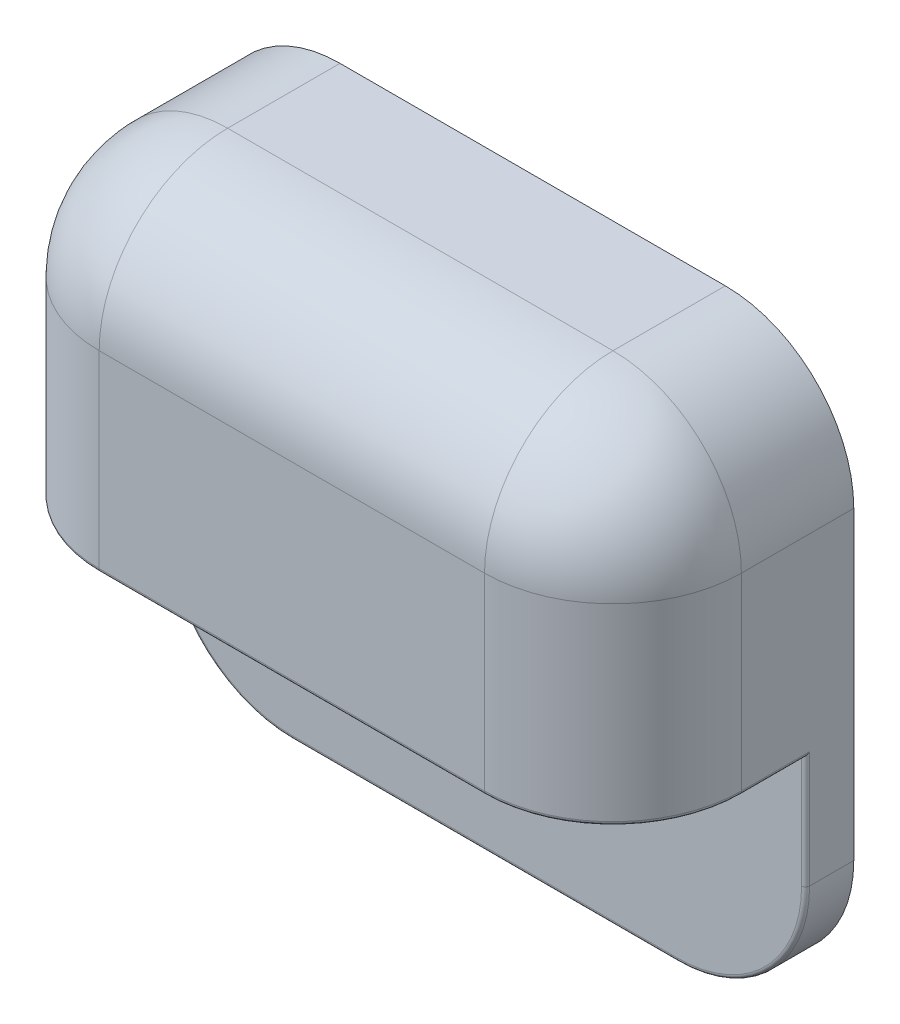
SolidWorks part; units mm, degrees
material "Plastique personnalisé"
ref_plane "Plan de face" through (0, 0, 0) normal (0, 0, 1) x (1, 0, 0)
ref_plane "Plan de dessus" through (0, 0, 0) normal (0, 1, 0) x (1, 0, 0)
ref_plane "Plan de droite" through (0, 0, 0) normal (1, 0, 0) x (0, 0, -1)
sketch "Esquisse1" plane through (0, 0, 0) normal (0, 0, 1) x (1, 0, 0)
  line L1 (-20, -10) -> (20, -10)
  line L2 (-20, -10) -> (-20, 10)
  line L3 (-20, 10) -> (20, 10)
  line L4 (20, -10) -> (20, 10)
  line L5 (-20, -10) -> (20, 10) construction
  line L6 (-20, 10) -> (20, -10) construction
  point P0 (0, 0)
  dimension "D1" = 20
  dimension "D2" = 40
extrude "Boss.-Extru.1" add sketch "Esquisse1" along normal blind 4 and the other way blind 8
sketch "Esquisse2" plane through (0, -10, 0) normal (0, -1, 0) x (1, 0, 0)
  line L0 (-20, -2) -> (20, -2) construction
  line L1 (-20, -8) -> (-20, 4) construction
  line L2 (20, -8) -> (20, 4) construction
  circle A0 centre (-13.7761, -2) radius 2.65
  circle A1 centre (-4.7761, -2) radius 2.65
  circle A2 centre (4.2239, -2) radius 2.65
  circle A3 centre (13.2239, -2) radius 2.65
  dimension "D1" = 4
extrude "Enlèv. mat.-Extru.1" cut sketch "Esquisse2" against normal blind 14.5
fillet "Congé1" radius 8 2 edges at (-20, 0, 4) (20, 0, 4)
fillet "Congé2" radius 0.25 4 edges at (13.2239, -10, -4.65) (4.2239, -10, -4.65) (-4.7761, -10, -4.65) (-13.7761, -10, -4.65)
sketch "Esquisse3" plane through (0, 0, -8) normal (0, 0, -1) x (-1, 0, 0)
  line L1 (20, 10) -> (-20, 10)
  line L2 (20, 10) -> (20, -25)
  line L3 (20, -25) -> (-20, -25)
  line L4 (-20, 10) -> (-20, -25)
  dimension "D1" = 35
extrude "Boss.-Extru.2" add sketch "Esquisse3" along normal blind 3
fillet "Congé3" radius 8 7 edges at (-20, 10, -7.5) (-17.6569, 10, 1.6569) (0, 10, 4) (20, 10, -7.5) (17.6569, 10, 1.6569) (-20, -25, -9.5) (20, -25, -9.5)
fillet "Congé4" radius 0.25 10 edges at (20, -10, -6) (-20, -10, -6) (-17.6569, -10, 1.6569) (0, -10, 4) (-20, -13.5, -8) (-17.6569, -22.6569, -8) (0, -25, -8) (20, -13.5, -8) (17.6569, -10, 1.6569) (17.6569, -22.6569, -8)
